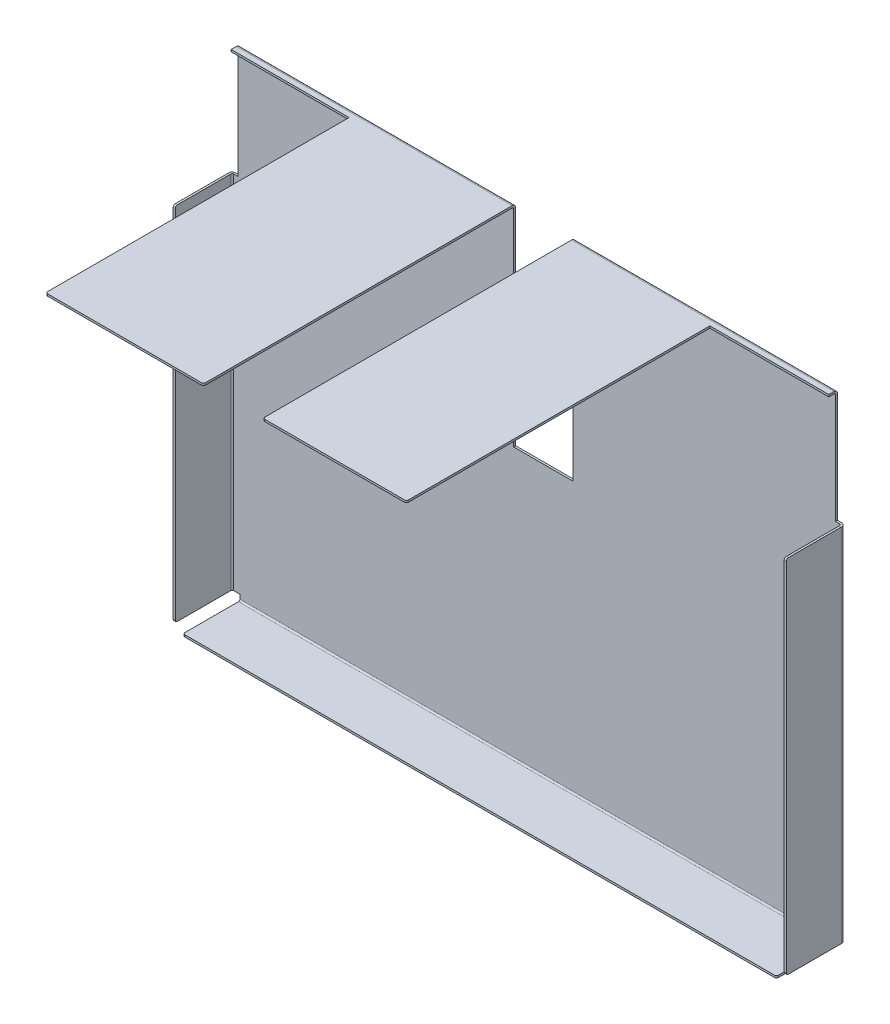
SolidWorks part; units mm, degrees
ref_plane "Front Plane" through (0, 0, 0) normal (0, 0, 1) x (1, 0, 0)
ref_plane "Top Plane" through (0, 0, 0) normal (0, 1, 0) x (1, 0, 0)
ref_plane "Right Plane" through (0, 0, 0) normal (1, 0, 0) x (0, 0, -1)
ref_plane "Plane1" through (0, 0, -1) normal (0, 0, -1) x (-1, 0, 0)
sketch "Sketch1" plane through (0, 0, -1) normal (0, 0, -1) x (-1, 0, 0)
  line L0 (326.2168, -163) -> (326.2168, 13)
  line L1 (326.2168, 13) -> (27.186, 13)
  line L2 (27.186, 13) -> (27.186, -163)
  line L3 (27.186, -163) -> (326.2168, -163)
extrude "Boss-Extrude1" add sketch "Sketch1" against normal blind 28.7654
sketch "Sketch2" plane through (0, -163, 0) normal (0, -1, 0) x (1, 0, 0)
  line L0 (-325.2168, 27.7654) -> (-325.2168, 0)
  line L1 (-325.2168, 0) -> (-28.186, 0)
  line L2 (-28.186, 0) -> (-28.186, 27.7654)
  line L3 (-28.186, 27.7654) -> (-325.2168, 27.7654)
extrude "Cut-Extrude1" cut sketch "Sketch2" against normal through all
sketch "Sketch3" plane through (0, 0, -1) normal (0, 0, -1) x (-1, 0, 0)
  line L0 (187.9514, 13) -> (158.9514, 13)
  line L1 (158.9514, 13) -> (158.9514, -34)
  line L2 (158.9514, -34) -> (187.9514, -34)
  line L3 (187.9514, -34) -> (187.9514, 13)
extrude "Cut-Extrude2" cut sketch "Sketch3" against normal through all
sketch "Sketch4" plane through (0, 13, 0) normal (0, 1, 0) x (-1, 0, 0)
  line L0 (322.4514, 0) -> (322.4514, -1)
  line L1 (322.4514, -1) -> (187.9514, -1)
  line L2 (187.9514, -1) -> (187.9514, 0)
  line L3 (187.9514, 0) -> (322.4514, 0)
extrude "Boss-Extrude2" add sketch "Sketch4" along normal blind 55.2654
sketch "Sketch5" plane through (0, 0, 0) normal (0, 0, 1) x (1, 0, 0)
  line L0 (-322.4514, 68.2654) -> (-187.9514, 68.2654)
  line L1 (-187.9514, 68.2654) -> (-187.9514, 67.2654)
  line L2 (-187.9514, 67.2654) -> (-322.4514, 67.2654)
  line L3 (-322.4514, 67.2654) -> (-322.4514, 68.2654)
extrude "Boss-Extrude3" add sketch "Sketch5" along normal blind 151.2654
sketch "Sketch6" plane through (0, 13, 0) normal (0, 1, 0) x (-1, 0, 0)
  line L0 (158.9514, 0) -> (158.9514, -1)
  line L1 (158.9514, -1) -> (30.9514, -1)
  line L2 (30.9514, -1) -> (30.9514, 0)
  line L3 (30.9514, 0) -> (158.9514, 0)
extrude "Boss-Extrude4" add sketch "Sketch6" along normal blind 55.2654
sketch "Sketch7" plane through (0, 0, 0) normal (0, 0, 1) x (1, 0, 0)
  line L0 (-158.9514, 68.2654) -> (-30.9514, 68.2654)
  line L1 (-30.9514, 68.2654) -> (-30.9514, 67.2654)
  line L2 (-30.9514, 67.2654) -> (-158.9514, 67.2654)
  line L3 (-158.9514, 67.2654) -> (-158.9514, 68.2654)
extrude "Boss-Extrude5" add sketch "Sketch7" along normal blind 151.2654
sketch "Sketch8" plane through (0, -163, 0) normal (0, -1, 0) x (1, 0, 0)
  line L0 (-31.9514, 0) -> (-31.9514, -1)
  line L1 (-31.9514, -1) -> (-321.4514, -1)
  line L2 (-321.4514, -1) -> (-321.4514, 0)
  line L3 (-321.4514, 0) -> (-31.9514, 0)
extrude "Boss-Extrude6" add sketch "Sketch8" along normal blind 3.7654
sketch "Sketch9" plane through (0, 0, 0) normal (0, 0, 1) x (1, 0, 0)
  line L0 (-321.4514, -165.7654) -> (-31.9514, -165.7654)
  line L1 (-31.9514, -165.7654) -> (-31.9514, -166.7654)
  line L2 (-31.9514, -166.7654) -> (-321.4514, -166.7654)
  line L3 (-321.4514, -166.7654) -> (-321.4514, -165.7654)
extrude "Boss-Extrude7" add sketch "Sketch9" along normal blind 27.7654
sketch "Sketch10" plane through (0, 67.2654, 0) normal (0, -1, 0) x (1, 0, 0)
  line L0 (-322.4514, 151.2654) -> (-322.4514, 3.2654)
  line L1 (-322.4514, 3.2654) -> (-264.9514, 3.2654)
  line L2 (-264.9514, 3.2654) -> (-264.9514, 151.2654)
  line L3 (-264.9514, 151.2654) -> (-322.4514, 151.2654)
extrude "Cut-Extrude3" cut sketch "Sketch10" against normal through all
sketch "Sketch11" plane through (0, 67.2654, 0) normal (0, -1, 0) x (1, 0, 0)
  line L0 (-88.9514, 151.2654) -> (-88.9514, 3.2654)
  line L1 (-88.9514, 3.2654) -> (-30.9514, 3.2654)
  line L2 (-30.9514, 3.2654) -> (-30.9514, 151.2654)
  line L3 (-30.9514, 151.2654) -> (-88.9514, 151.2654)
extrude "Cut-Extrude4" cut sketch "Sketch11" against normal through all
fillet "Fillet1" radius 0.7366 5 edges at (-28.186, -75, 0) (-325.2168, -75, 0) (-176.7014, -165.7654, 0) (-255.2014, 67.2654, 0) (-94.9514, 67.2654, 0)
fillet "Fillet2" radius 1 10 edges at (-158.9514, 67.7654, 151.2654) (-264.9514, 67.7654, 151.2654) (-325.7168, -163, 27.7654) (-325.7168, 13, 27.7654) (-187.9514, 67.7654, 151.2654) (-27.686, -163, 27.7654) (-88.9514, 67.7654, 151.2654) (-31.9514, -166.2654, 27.7654) (-27.686, 13, 27.7654) (-321.4514, -166.2654, 27.7654)
fillet "Fillet3" radius 1.7366 5 edges at (-326.2168, -75, -1) (-176.7014, -166.7654, -1) (-255.2014, 68.2654, -1) (-94.9514, 68.2654, -1) (-27.186, -75, -1)
